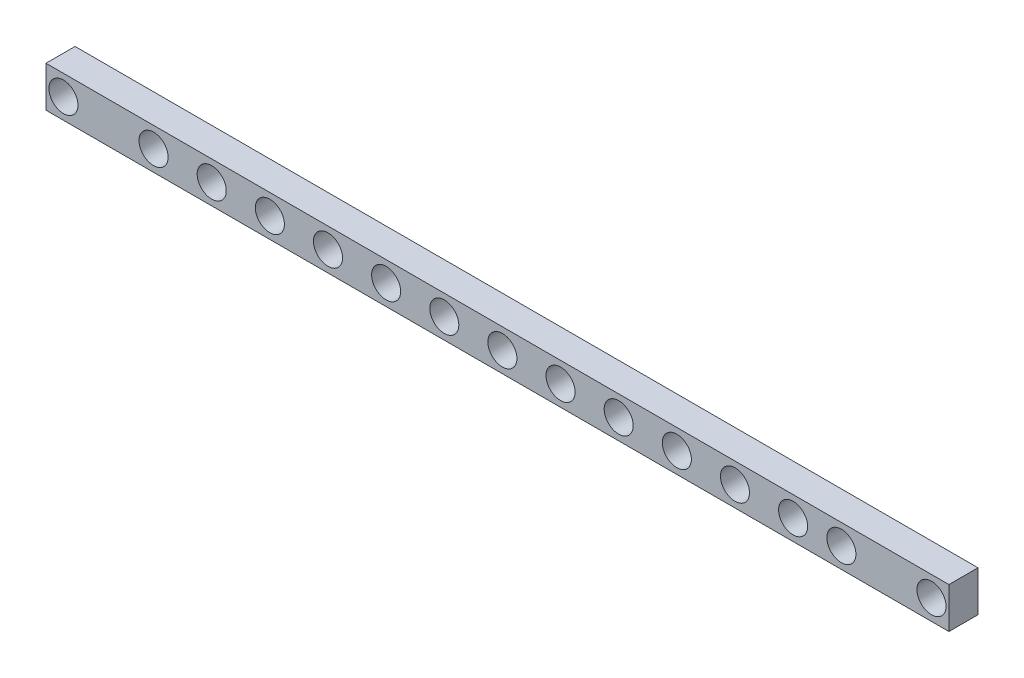
SolidWorks part; units mm, degrees
ref_plane "Front Plane" through (0, 0, 0) normal (0, 0, 1) x (1, 0, 0)
ref_plane "Top Plane" through (0, 0, 0) normal (0, 1, 0) x (1, 0, 0)
ref_plane "Right Plane" through (0, 0, 0) normal (1, 0, 0) x (0, 0, -1)
sketch "Sketch1" plane through (0, 0, 0) normal (0, 0, 1) x (1, 0, 0)
  line L0 (0, 0) -> (0, -0.35) construction
  line L1 (-7.765, 0.35) -> (7.765, 0.35)
  line L2 (-7.765, 0.35) -> (-7.765, -0.35)
  line L3 (-7.765, -0.35) -> (7.765, -0.35)
  line L4 (7.765, 0.35) -> (7.765, -0.35)
  line L5 (-7.765, 0.35) -> (7.765, -0.35) construction
  line L6 (-7.765, -0.35) -> (7.765, 0.35) construction
  circle A0 centre (-7.465, 0) radius 0.25
  circle A1 centre (-5.915, 0) radius 0.25
  circle A2 centre (5.915, 0) radius 0.25
  circle A3 centre (7.465, 0) radius 0.25
  circle A4 centre (-4.915, 0) radius 0.25
  circle A5 centre (-3.915, 0) radius 0.25
  circle A6 centre (-2.915, 0) radius 0.25
  circle A7 centre (-1.915, 0) radius 0.25
  circle A8 centre (-0.915, 0) radius 0.25
  circle A9 centre (0.085, 0) radius 0.25
  circle A10 centre (1.085, 0) radius 0.25
  circle A11 centre (2.085, 0) radius 0.25
  circle A12 centre (3.085, 0) radius 0.25
  circle A13 centre (4.085, 0) radius 0.25
  circle A14 centre (5.085, 0) radius 0.25
  point P0 (0, 0)
  dimension "D3" = 0.3
  dimension "D1" = 15.53
  dimension "D2" = 0.7
  dimension "D4" = 2
  dimension "D5" = 12
extrude "Boss-Extrude1" add sketch "Sketch1" along normal blind 0.5
